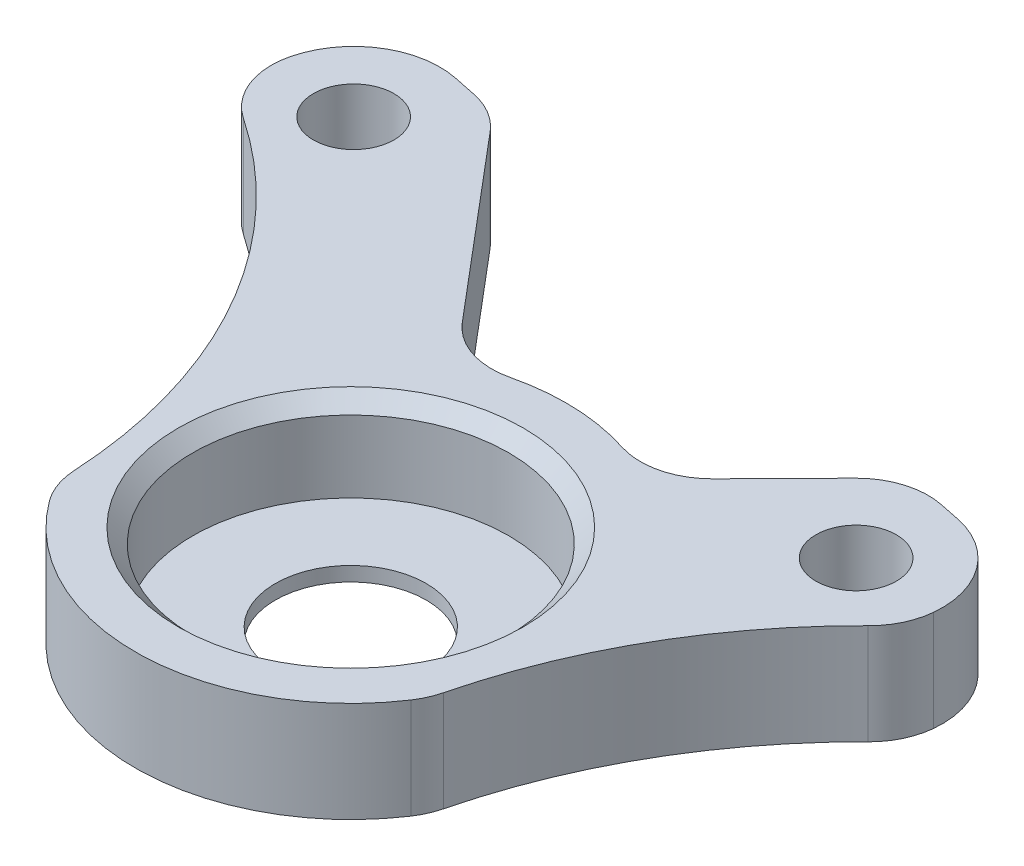
SolidWorks part; units mm, degrees
ref_plane "Front Plane" through (0, 0, 0) normal (0, 0, 1) x (1, 0, 0)
ref_plane "Top Plane" through (0, 0, 0) normal (0, 1, 0) x (1, 0, 0)
ref_plane "Right Plane" through (0, 0, 0) normal (1, 0, 0) x (0, 0, -1)
sketch "Sketch1" plane through (0, 0, 0) normal (0, 1, 0) x (1, 0, 0)
  line L0 (-13.0075, -7.4703) -> (-29.8521, 21.8598)
  line L1 (-23.4352, 30.7239) -> (20.6342, 21.6193)
  line L2 (24.6232, 12.7553) -> (13.0075, -7.4703)
  line L3 (-24.6491, 24.848) -> (0, 0) construction
  line L4 (0, 0) -> (19.4202, 15.7434) construction
  line L5 (19.4202, 15.7434) -> (-24.6491, 24.848) construction
  circle A0 centre (0, 0) radius 11
  arc A1 (-13.0075, -7.4703) -> (13.0075, -7.4703) centre (0, 0) ccw
  arc A2 (20.6342, 21.6193) -> (24.6232, 12.7553) centre (19.4202, 15.7434) cw
  arc A3 (-29.8521, 21.8598) -> (-23.4352, 30.7239) centre (-24.6491, 24.848) cw
  circle A4 centre (-24.6491, 24.848) radius 2.8
  circle A5 centre (19.4202, 15.7434) radius 2.8
  point P6 (0, 0)
  dimension "D1" = 22
  dimension "D2" = 15
  dimension "D3" = 6
  dimension "D4" = 35
  dimension "D6" = 5.6
  dimension "D8" = 5.6
  dimension "D5" = 45
  dimension "D7" = 25
extrude "Boss-Extrude1" add sketch "Sketch1" along normal blind 6
sketch "Sketch6" plane through (0, 6, 0) normal (0, 1, 0) x (1, 0, 0)
  line L0 (-6.2716, 13.626) -> (-20.1351, 30.0421)
  line L1 (20.6342, 21.6193) -> (-23.4352, 30.7239) construction
  line L2 (7.2888, 13.1101) -> (16.5022, 22.473)
  line L3 (-20.1351, 30.0421) -> (16.5022, 22.473)
  line L4 (-22.5099, 26.6546) -> (-9.3277, 11.0451) construction
  line L5 (-9.3277, 11.0451) -> (-6.2716, 13.626) construction
  line L6 (-9.3277, 11.0451) -> (0, 0) construction
  line L7 (17.4245, 17.7073) -> (0, 0) construction
  line L8 (7.2888, 13.1101) -> (10.1399, 10.3045) construction
  arc A1 (-6.2716, 13.626) -> (7.2888, 13.1101) centre (0, 0) cw
  circle A2 centre (-24.6491, 24.848) radius 2.8 construction
  circle A3 centre (19.4202, 15.7434) radius 2.8 construction
  point P9 (18.2038, 18.2654)
  dimension "D1" = 15
  dimension "D2" = 4
  dimension "D3" = 4
extrude "Cut-Extrude4" cut sketch "Sketch6" against normal up to next
chamfer "Chamfer1" distance 1 angle 45 1 edges at (0, 6, 11)
sketch "Sketch5" plane through (0, 6, 0) normal (0, 1, 0) x (1, 0, 0)
  line L1 (-29.8521, 21.8598) -> (-13.0075, -7.4703) construction
  line L2 (-29.8521, 21.8598) -> (-13.0075, -7.4703)
  line L4 (13.0075, -7.4703) -> (24.6232, 12.7553) construction
  line L5 (13.0075, -7.4703) -> (24.6232, 12.7553)
  arc A0 (-29.8521, 21.8598) -> (-13.0075, -7.4703) centre (-48.0024, -8.0662) cw
  arc A1 (24.6232, 12.7553) -> (13.0075, -7.4703) centre (51.995, -16.413) ccw
  dimension "D1" = 35
  dimension "D2" = 40
extrude "Cut-Extrude3" cut sketch "Sketch5" against normal through all
sketch "Sketch4" plane through (0, 0, 0) normal (0, -1, 0) x (1, 0, 0)
  line L1 (16.5022, -22.473) -> (20.6342, -21.6193)
  line L2 (16.5022, -22.473) -> (20.6342, -21.6193)
  line L6 (-23.4352, -30.7239) -> (-20.1351, -30.0421)
  line L7 (-23.4352, -30.7239) -> (-20.1351, -30.0421)
  line L10 (-20.1351, -30.0421) -> (-6.2716, -13.626)
  line L11 (-20.1351, -30.0421) -> (-6.2716, -13.626)
  line L12 (7.2888, -13.1101) -> (16.5022, -22.473)
  line L13 (7.2888, -13.1101) -> (16.5022, -22.473)
  circle A0 centre (19.4202, -15.7434) radius 2.8 construction
  circle A1 centre (-24.6491, -24.848) radius 2.8 construction
  circle A2 centre (19.4202, -15.7434) radius 2.8
  circle A3 centre (-24.6491, -24.848) radius 2.8
  circle A4 centre (0, 0) radius 5.25
  arc A6 (-29.8521, -21.8598) -> (-23.4352, -30.7239) centre (-24.6491, -24.848) ccw
  arc A10 (20.6342, -21.6193) -> (24.6232, -12.7553) centre (19.4202, -15.7434) ccw
  arc A11 (13.0075, 7.4703) -> (-13.0075, 7.4703) centre (0, 0) ccw
  arc A12 (-29.8521, -21.8598) -> (-23.4352, -30.7239) centre (-24.6491, -24.848) ccw
  arc A16 (20.6342, -21.6193) -> (24.6232, -12.7553) centre (19.4202, -15.7434) ccw
  arc A17 (13.0075, 7.4703) -> (-13.0075, 7.4703) centre (0, 0) ccw
  arc A20 (-6.2716, -13.626) -> (7.2888, -13.1101) centre (0, 0) ccw
  arc A21 (-6.2716, -13.626) -> (7.2888, -13.1101) centre (0, 0) ccw
  arc A24 (-29.8521, -21.8598) -> (-13.0075, 7.4703) centre (-48.0024, 8.0662) ccw
  arc A25 (-29.8521, -21.8598) -> (-13.0075, 7.4703) centre (-48.0024, 8.0662) ccw
  arc A33 (13.0075, 7.4703) -> (24.6232, -12.7553) centre (51.995, 16.413) ccw
  arc A34 (13.0075, 7.4703) -> (24.6232, -12.7553) centre (51.995, 16.413) ccw
  dimension "D2" = 10.5
  dimension "D1" = 0
extrude "Boss-Extrude2" add sketch "Sketch4" along normal blind 1
fillet "Fillet1" radius 5 8 edges at (-20.1351, 2.5, -30.0421) (-6.2716, 2.5, -13.626) (7.2888, 2.5, -13.1101) (16.5022, 2.5, -22.473) (13.0075, 2.5, 7.4703) (-13.0075, 2.5, 7.4703) (24.6232, 2.5, -12.7553) (-29.8521, 2.5, -21.8598)
